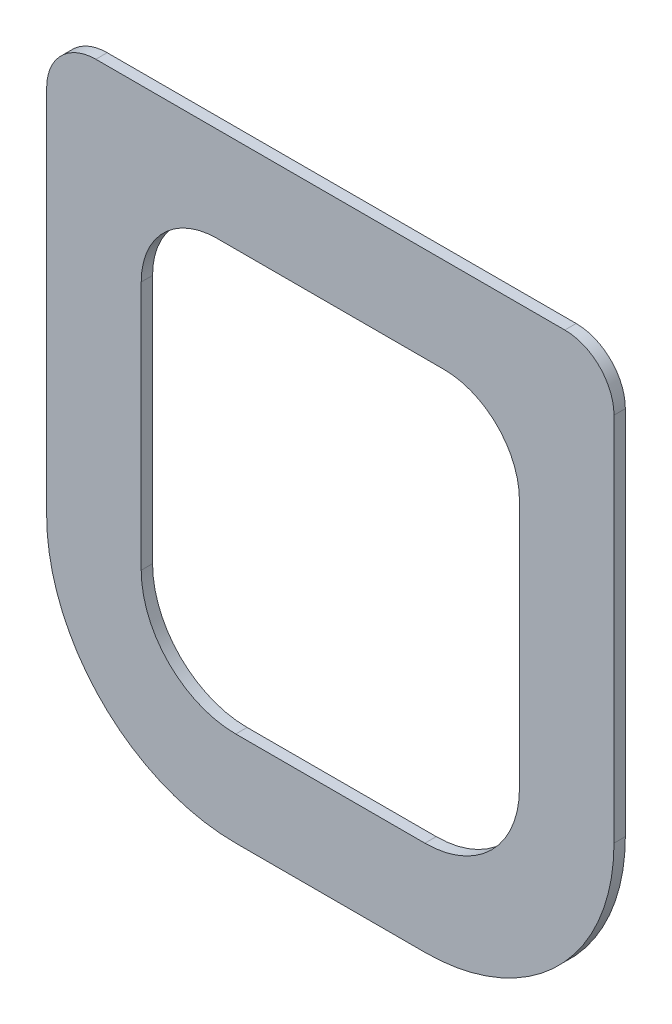
SolidWorks part; units mm, degrees
ref_plane "Front Plane" through (0, 0, 0) normal (0, 0, 1) x (1, 0, 0)
ref_plane "Top Plane" through (0, 0, 0) normal (0, 1, 0) x (1, 0, 0)
ref_plane "Right Plane" through (0, 0, 0) normal (1, 0, 0) x (0, 0, -1)
sketch "Sketch1" plane through (0, 0, 0) normal (0, 0, 1) x (1, 0, 0)
  line L0 (-0.5, -84.19) -> (0.5, -84.19)
  line L1 (75, -34.19) -> (75, 63.81)
  line L2 (-25, -84.19) -> (-0.5, -84.19)
  line L3 (0.5, -84.19) -> (25, -84.19)
  line L4 (62, 76.81) -> (-62, 76.81)
  line L5 (75, 63.81) -> (-75, 63.81) construction
  line L6 (-75, 63.81) -> (-75, -34.19)
  line L7 (50, 51.81) -> (-50, 51.81)
  line L8 (-50, 51.81) -> (-50, -34.19)
  line L9 (-25, -59.19) -> (-0.5, -59.19)
  line L10 (-0.5, -59.19) -> (0.5, -59.19)
  line L11 (0.5, -59.19) -> (25, -59.19)
  line L12 (50, -34.19) -> (50, 51.81)
  arc A0 (25, -84.19) -> (75, -34.19) centre (25, -34.19) ccw
  arc A1 (-75, -34.19) -> (-25, -84.19) centre (-25, -34.19) ccw
  arc A2 (75, 63.81) -> (62, 76.81) centre (62, 63.81) ccw
  arc A3 (-75, 63.81) -> (-62, 76.81) centre (-62, 63.81) cw
  arc A4 (-50, 51.81) -> (-50, 51.81) centre (-50, 51.81) cw
  arc A5 (-50, -34.19) -> (-25, -59.19) centre (-25, -34.19) ccw
  arc A6 (25, -59.19) -> (50, -34.19) centre (25, -34.19) ccw
  arc A7 (50, 51.81) -> (50, 51.81) centre (50, 51.81) ccw
  point P2 (0, 76.81)
  point P31 (0, 0)
  dimension "D1" = 13
  dimension "D2" = 98
  dimension "D3" = 150
  dimension "D4" = 76.81
  dimension "D5" = 25
extrude "Boss-Extrude1" add sketch "Sketch1" along normal blind 3
fillet "Fillet1" radius 20 2 edges at (50, 51.81, 1.5) (-50, 51.81, 1.5)
